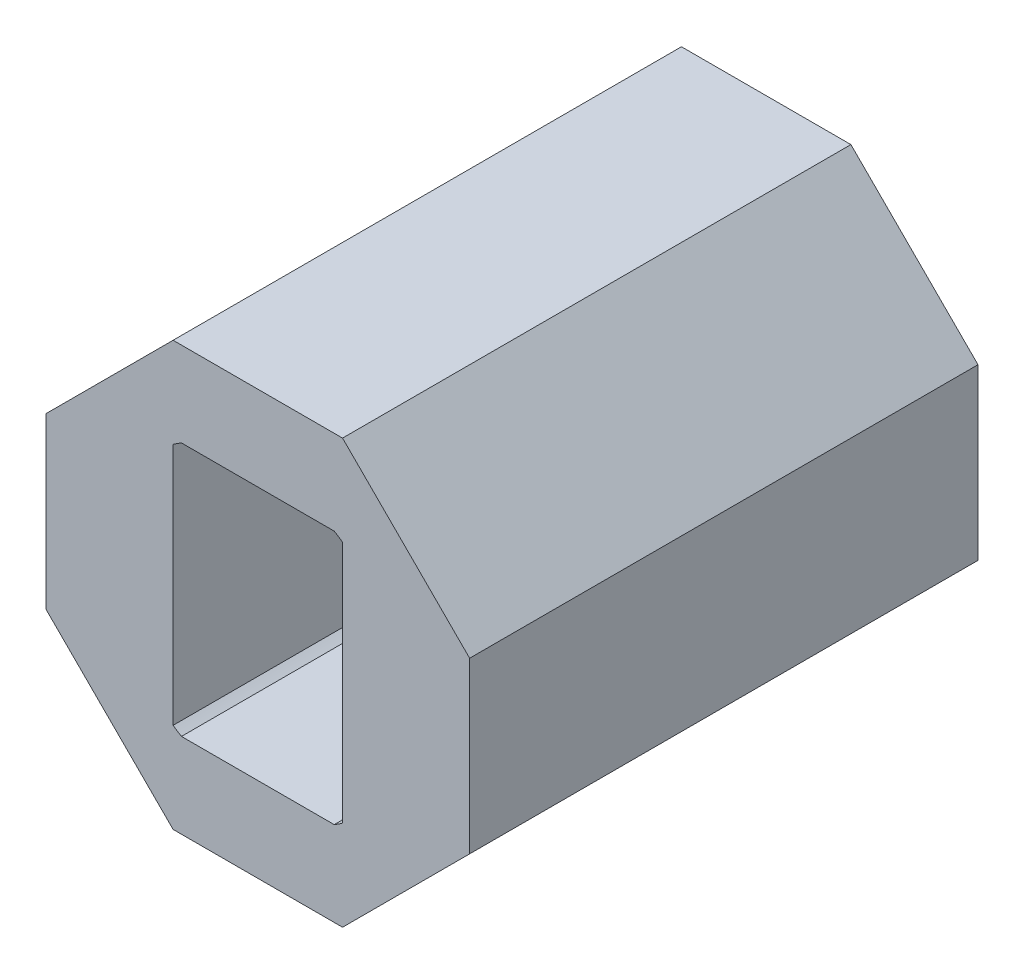
SolidWorks part; units mm, degrees
ref_plane "Front Plane" through (0, 0, 0) normal (1, 0, 0) x (0, 1, 0)
ref_plane "Top Plane" through (0, 0, 0) normal (0, 0, 1) x (0, 1, 0)
ref_plane "Right Plane" through (0, 0, 0) normal (0, 1, 0) x (-1, 0, 0)
sketch "Sketch1" plane through (0, 0, 0) normal (0, 0, 1) x (0, 1, 0)
  line L0 (3, 0) -> (0, -3)
  line L1 (3, 0) -> (7, 0)
  line L2 (0, -3) -> (0, -7)
  line L3 (3, -10) -> (7, -10)
  line L4 (10, -3) -> (10, -7)
  line L5 (0, -7) -> (3, -10)
  line L6 (7, -10) -> (10, -7)
  line L7 (10, -3) -> (7, 0)
  line L9 (2.1277, -3) -> (7.8723, -3)
  line L10 (2, -3.1972) -> (2, -6.8028)
  line L11 (2.1277, -7) -> (7.8723, -7)
  line L12 (8, -3.1972) -> (8, -6.8028)
  circle A0 centre (5, -5) radius 3.5
  dimension "D11" = 7
  dimension "D3" = 4
  dimension "D4" = 4
  dimension "D5" = 4
  dimension "D6" = 4
  dimension "D13" = 2
  dimension "D14" = 5
  dimension "D16" = 3
extrude "Boss-Extrude1" add sketch "Sketch1" along normal blind 12 contours L4 L7 L1 L0 L2 L5 L3 L6 A0 | L9 A0 | L11 A0 | L10 A0 | L12 A0
sketch "Sketch2" plane through (0, 0, 12) normal (0, 0, 1) x (1, 0, 0)
  circle A0 centre (5, 5) radius 2
